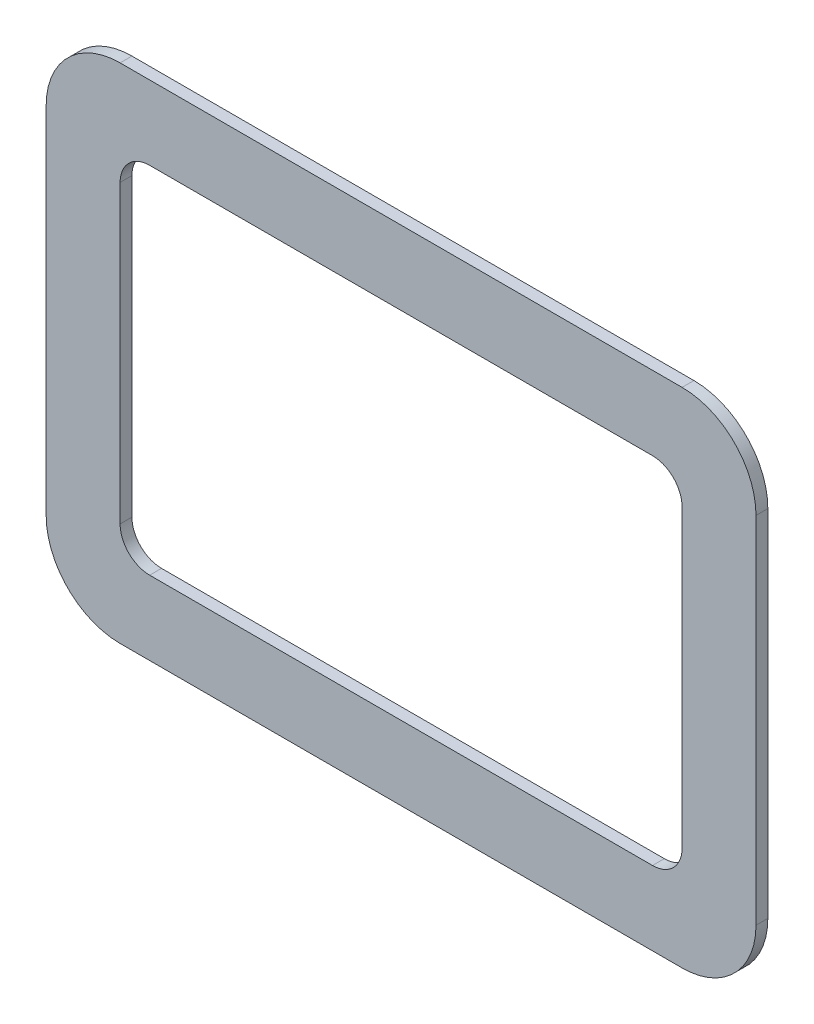
SolidWorks part; units mm, degrees
ref_plane "Спереди" through (0, 0, 0) normal (0, 0, 1) x (1, 0, 0)
ref_plane "Сверху" through (0, 0, 0) normal (0, 1, 0) x (1, 0, 0)
ref_plane "Справа" through (0, 0, 0) normal (1, 0, 0) x (0, 0, -1)
sketch "Эскиз1" plane through (0, 0, 0) normal (0, 0, 1) x (1, 0, 0)
  line L1 (-19, 17) -> (19, 17)
  line L2 (-24, 12) -> (-24, -12)
  line L3 (-19, -17) -> (19, -17)
  line L4 (24, 12) -> (24, -12)
  line L5 (-24, 17) -> (24, -17) construction
  line L6 (-24, -17) -> (24, 17) construction
  line L7 (-17, 12) -> (17, 12)
  line L8 (-19, 10) -> (-19, -10)
  line L9 (-17, -12) -> (17, -12)
  line L10 (19, 10) -> (19, -10)
  line L11 (-19, 12) -> (19, -12) construction
  line L12 (-19, -12) -> (19, 12) construction
  arc A0 (-24, -12) -> (-19, -17) centre (-19, -12) ccw
  arc A1 (19, -17) -> (24, -12) centre (19, -12) ccw
  arc A2 (19, 17) -> (24, 12) centre (19, 12) cw
  arc A3 (-19, 17) -> (-24, 12) centre (-19, 12) ccw
  arc A4 (-17, 12) -> (-19, 10) centre (-17, 10) ccw
  arc A5 (-19, -10) -> (-17, -12) centre (-17, -10) ccw
  arc A6 (17, -12) -> (19, -10) centre (17, -10) ccw
  arc A7 (17, 12) -> (19, 10) centre (17, 10) cw
  point P0 (0, 0)
  point P18 (0, 0)
  dimension "D3" = 5
  dimension "D6" = 2
  dimension "D1" = 48
  dimension "D2" = 34
  dimension "D4" = 5
  dimension "D5" = 5
extrude "Бобышка-Вытянуть1" add sketch "Эскиз1" along normal blind 0.8
